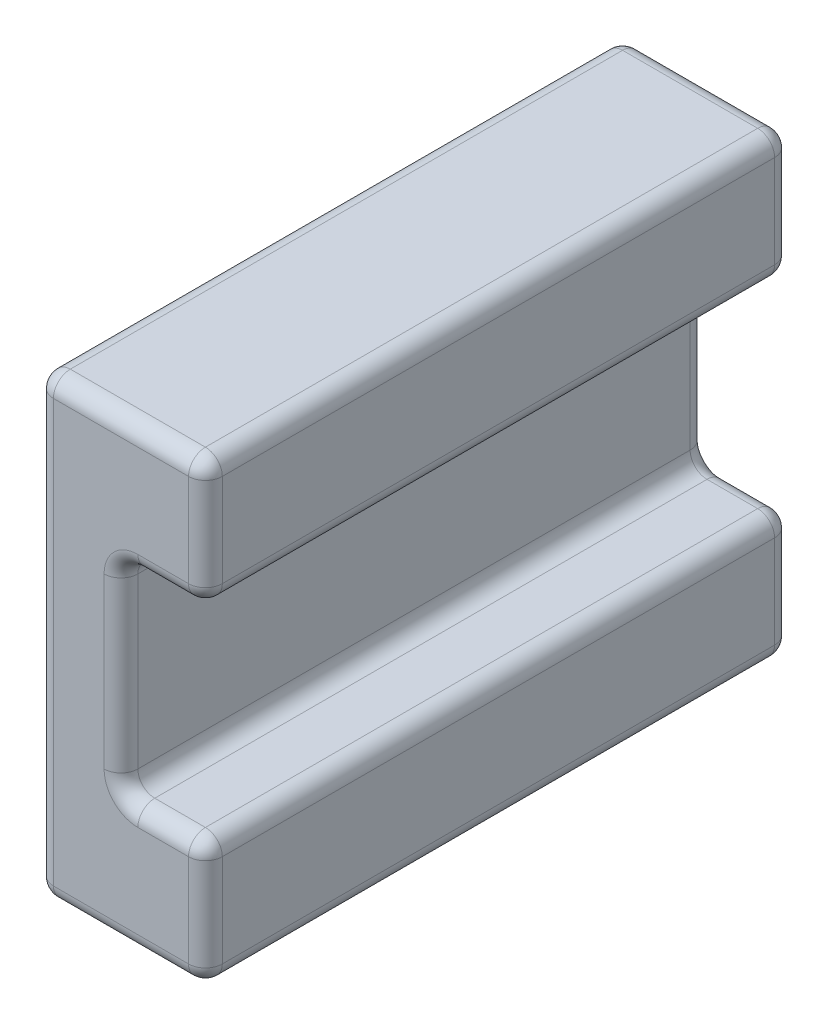
SolidWorks part; units mm, degrees
ref_plane "Front Plane" through (0, 0, 0) normal (0, 0, 1) x (1, 0, 0)
ref_plane "Top Plane" through (0, 0, 0) normal (0, 1, 0) x (1, 0, 0)
ref_plane "Right Plane" through (0, 0, 0) normal (1, 0, 0) x (0, 0, -1)
sketch "Sketch1" plane through (0, 0, 0) normal (0, 0, 1) x (1, 0, 0)
  line L0 (5, -6) -> (5, -13.5)
  line L1 (-5, 13.5) -> (5, 13.5)
  line L2 (-5, 13.5) -> (-5, -13.5)
  line L3 (-5, -13.5) -> (5, -13.5)
  line L4 (5, 13.5) -> (5, 6)
  line L5 (-5, 13.5) -> (5, -13.5) construction
  line L6 (-5, -13.5) -> (5, 13.5) construction
  line L7 (0, -6) -> (5, -6)
  line L8 (0, -6) -> (0, 6)
  line L9 (0, 6) -> (5, 6)
  line L11 (0, -6) -> (5, 0) construction
  line L12 (0, 6) -> (5, 0) construction
  point P0 (0, 0)
  point P6 (5, 0)
  dimension "D1" = 27
  dimension "D2" = 10
  dimension "D3" = 12
  dimension "D4" = 5
extrude "Boss-Extrude1" add sketch "Sketch1" along normal blind 34.7
sketch "Sketch3" plane through (-5, 0, 0) normal (-1, 0, 0) x (0, 0, 1)
  line L0 (0, 0) -> (5.5023, 0) construction
  line L1 (17.35, 15.8594) -> (17.35, 13.4331) construction
  circle A0 centre (9.85, 10) radius 1.7
  circle A1 centre (24.85, 10) radius 1.7
  circle A2 centre (24.85, -10) radius 1.7
  circle A3 centre (9.85, -10) radius 1.7
  dimension "D1" = 3.4
  dimension "D2" = 15
  dimension "D3" = 20
fillet "Fillet1" radius 1 24 edges at (-5, -13.5, 17.35) (2.5, -6, 0) (2.5, 6, 0) (-5, 0, 0) (0, -13.5, 0) (-5, 0, 34.7) (2.5, 6, 34.7) (2.5, -6, 34.7) (0, -13.5, 34.7) (0, -6, 17.35) (0, 0, 34.7) (0, 6, 17.35) (0, 0, 0) (5, -13.5, 17.35) (5, -9.75, 34.7) (5, -6, 17.35) (5, -9.75, 0) (5, 6, 17.35) (5, 9.75, 34.7) (5, 9.75, 0) (5, 13.5, 17.35) (0, 13.5, 34.7) (-5, 13.5, 17.35) (0, 13.5, 0)
hole_wizard "M3 Tapped Hole2" positions "3DSketch2" profile "Sketch5" tap size "M3" standard "ISO"
sketch3d "3DSketch2"
  point P0 (-5, 10, 9.85)
  point P3 (-5, 10, 24.85)
  point P6 (-5, -10, 24.85)
  point P9 (-5, -10, 9.85)
sketch "Sketch5" plane through (-5, 10, 9.85) normal (0, 1, 0) x (0, 0, 1)
  line L0 (0, 0) -> (0, 5)
  line L1 (0, 5) -> (1.25, 4.2489)
  line L2 (1.25, 4.2489) -> (1.25, 0.275)
  line L3 (1.25, 0.275) -> (1.525, 0)
  line L5 (1.525, 0) -> (0, 0)
  line L6 (-1.25, 0.275) -> (-1.525, 0) construction
  line L10 (0, 5) -> (-1.25, 4.2489) construction
  line L11 (0, -6.35) -> (0, 107.95) construction
  dimension "Tap Drill Dia." = 2.5
  dimension "Tap Drill Depth" = 5
  dimension "Near C'Sink Dia." = 3.05
  dimension "Near C'Sink Angle" = 90
  dimension "Drill Angle" = 118
cosmetic thread "Hole Thread5" parameters "D1"=6, "D2"=3
cosmetic thread "Hole Thread6" parameters "D1"=6, "D2"=3
cosmetic thread "Hole Thread7" parameters "D1"=6, "D2"=3
cosmetic thread "Hole Thread8" parameters "D1"=6, "D2"=3
sketch "Sketch6" plane through (-5, 0, 0) normal (-1, 0, 0) x (0, 0, 1)
  circle A0 centre (9.85, -10) radius 1.525 construction
  circle A1 centre (24.85, -10) radius 1.525 construction
  circle A2 centre (24.85, 10) radius 1.525 construction
  circle A3 centre (9.85, 10) radius 1.525 construction
  circle A4 centre (9.85, -10) radius 1.525
  circle A5 centre (24.85, -10) radius 1.525
  circle A6 centre (24.85, 10) radius 1.525
  circle A7 centre (9.85, 10) radius 1.525
